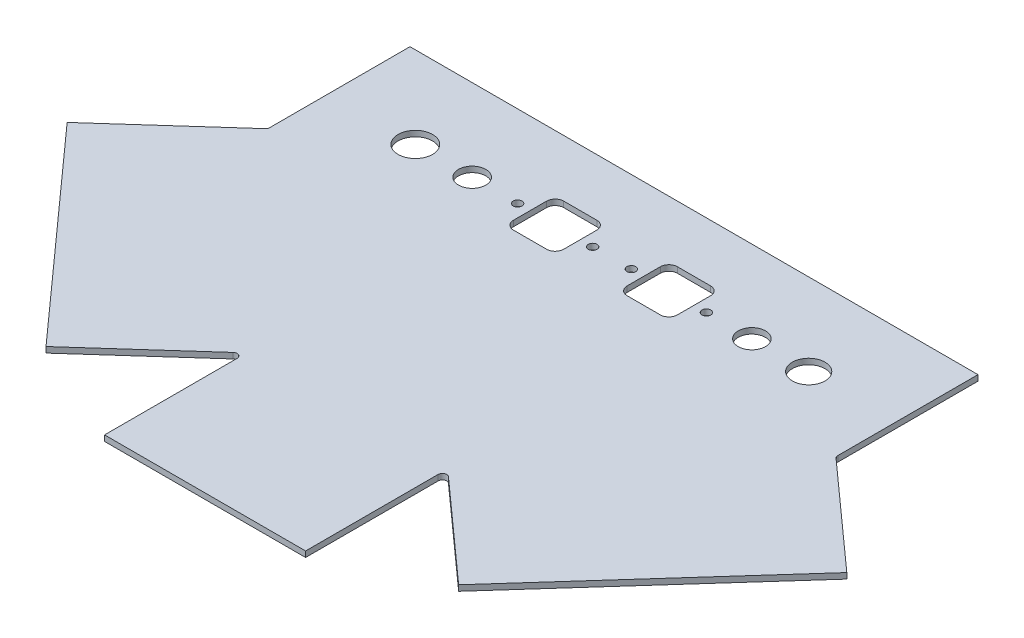
SolidWorks part; units mm, degrees
ref_plane "Front Plane" through (0, 0, 0) normal (0, 0, 1) x (1, 0, 0)
ref_plane "Top Plane" through (0, 0, 0) normal (0, 1, 0) x (1, 0, 0)
ref_plane "Right Plane" through (0, 0, 0) normal (1, 0, 0) x (0, 0, -1)
sketch "Sketch1" plane through (0, 0, 0) normal (0, 1, 0) x (1, 0, 0)
  line L0 (-56.134, 0) -> (56.134, 0) construction
  line L1 (56.134, 0) -> (158.623, 114.3) construction
  line L2 (158.623, 114.3) -> (-158.623, 114.3) construction
  line L3 (-158.623, 114.3) -> (-56.134, 0) construction
  line L4 (0, 0) -> (0, 50000) construction
  line L5 (-158.623, 114.3) -> (-217.7198, 61.3098)
  line L7 (-158.623, 114.3) -> (-158.623, 193.675)
  line L8 (-158.623, 193.675) -> (158.623, 193.675)
  line L9 (158.623, 114.3) -> (158.623, 193.675)
  line L10 (-217.7198, 61.3098) -> (-115.2308, -52.9902)
  line L11 (-115.2308, -52.9902) -> (-56.134, 0)
  line L12 (56.134, 0) -> (115.2308, -52.9902)
  line L13 (115.2308, -52.9902) -> (217.7198, 61.3098)
  line L14 (217.7198, 61.3098) -> (158.623, 114.3)
  line L15 (56.134, 0) -> (56.134, -79.375)
  line L16 (56.134, -79.375) -> (-56.134, -79.375)
  line L17 (-56.134, -79.375) -> (-56.134, 0)
  point P7 (0, 0)
  point P8 (0, 114.3)
  dimension "D1" = 112.268
  dimension "D2" = 317.246
  dimension "D3" = 114.3
  dimension "D4" = 79.375
  dimension "D5" = 48.118
  dimension "D6" = 131.882
extrude "Boss-Extrude1" add sketch "Sketch1" along normal blind 3.175
fillet "Fillet1" radius 2.3813 4 edges at (-158.623, 1.5875, -114.3) (158.623, 1.5875, -114.3) (56.134, 1.5875, 0) (-56.134, 1.5875, 0)
sketch "Sketch2" plane through (0, 3.175, 0) normal (0, 1, 0) x (1, 0, 0)
  line L0 (10.795, 147.8915) -> (52.705, 147.8915) construction
  line L1 (17.7165, 161.925) -> (45.7835, 161.925) construction
  line L2 (17.7165, 161.925) -> (17.7165, 133.858) construction
  line L3 (17.7165, 133.858) -> (45.7835, 133.858) construction
  line L4 (45.7835, 161.925) -> (45.7835, 133.858) construction
  line L5 (31.75, 161.925) -> (31.75, 133.858) construction
  line L6 (17.7165, 157.1498) -> (17.7165, 138.6332)
  line L7 (22.4917, 133.858) -> (41.0083, 133.858)
  line L8 (45.7835, 138.6332) -> (45.7835, 157.1498)
  line L9 (41.0083, 161.925) -> (22.4917, 161.925)
  line L10 (-10.795, 147.8915) -> (10.795, 147.8915) construction
  line L11 (-52.705, 147.8915) -> (-10.795, 147.8915) construction
  line L12 (-45.7835, 161.925) -> (-17.7165, 161.925) construction
  line L13 (-45.7835, 161.925) -> (-45.7835, 133.858) construction
  line L14 (-45.7835, 133.858) -> (-17.7165, 133.858) construction
  line L15 (-17.7165, 161.925) -> (-17.7165, 133.858) construction
  line L16 (-31.75, 161.925) -> (-31.75, 133.858) construction
  line L17 (-45.7835, 157.1498) -> (-45.7835, 138.6332)
  line L18 (-41.0083, 133.858) -> (-22.4917, 133.858)
  line L19 (-17.7165, 138.6332) -> (-17.7165, 157.1498)
  line L20 (-22.4917, 161.925) -> (-41.0083, 161.925)
  line L21 (0, 0) -> (0, 147.8915) construction
  line L22 (158.623, 193.675) -> (-158.623, 193.675) construction
  circle A0 centre (52.705, 147.8915) radius 2.4511
  circle A1 centre (10.795, 147.8915) radius 2.4511
  arc A2 (17.7165, 138.6332) -> (22.4917, 133.858) centre (22.4917, 138.6332) ccw
  arc A3 (41.0083, 133.858) -> (45.7835, 138.6332) centre (41.0083, 138.6332) ccw
  arc A4 (45.7835, 157.1498) -> (41.0083, 161.925) centre (41.0083, 157.1498) ccw
  arc A5 (22.4917, 161.925) -> (17.7165, 157.1498) centre (22.4917, 157.1498) ccw
  circle A6 centre (-10.795, 147.8915) radius 2.4511
  circle A7 centre (-52.705, 147.8915) radius 2.4511
  arc A8 (-45.7835, 138.6332) -> (-41.0083, 133.858) centre (-41.0083, 138.6332) ccw
  arc A9 (-22.4917, 133.858) -> (-17.7165, 138.6332) centre (-22.4917, 138.6332) ccw
  arc A10 (-17.7165, 157.1498) -> (-22.4917, 161.925) centre (-22.4917, 157.1498) ccw
  arc A11 (-41.0083, 161.925) -> (-45.7835, 157.1498) centre (-41.0083, 157.1498) ccw
  circle A12 centre (-109.855, 147.8915) radius 9.652
  circle A13 centre (-78.105, 147.8915) radius 7.62
  circle A14 centre (78.105, 147.8915) radius 7.62
  circle A15 centre (109.855, 147.8915) radius 9.1186
  point P10 (31.75, 147.8915)
  point P11 (31.75, 147.8915)
  point P24 (31.75, 161.925)
  point P44 (-31.75, 147.8915)
  point P45 (-31.75, 147.8915)
  point P58 (-31.75, 161.925)
  dimension "D3" = 4.9022
  dimension "D4" = 4.9022
  dimension "D6" = 4.7752
  dimension "D8" = 4.7752
  dimension "D9" = 19.304
  dimension "D10" = 15.24
  dimension "D14" = 18.2372
  dimension "D1" = 28.067
  dimension "D2" = 41.91
  dimension "D5" = 41.91
  dimension "D7" = 28.067
  dimension "D11" = 25.4
  dimension "D12" = 25.4
  dimension "D13" = 31.75
  dimension "D15" = 31.75
  dimension "D16" = 63.5
  dimension "D17" = 31.75
extrude "Cut-Extrude1" cut sketch "Sketch2" against normal through all
